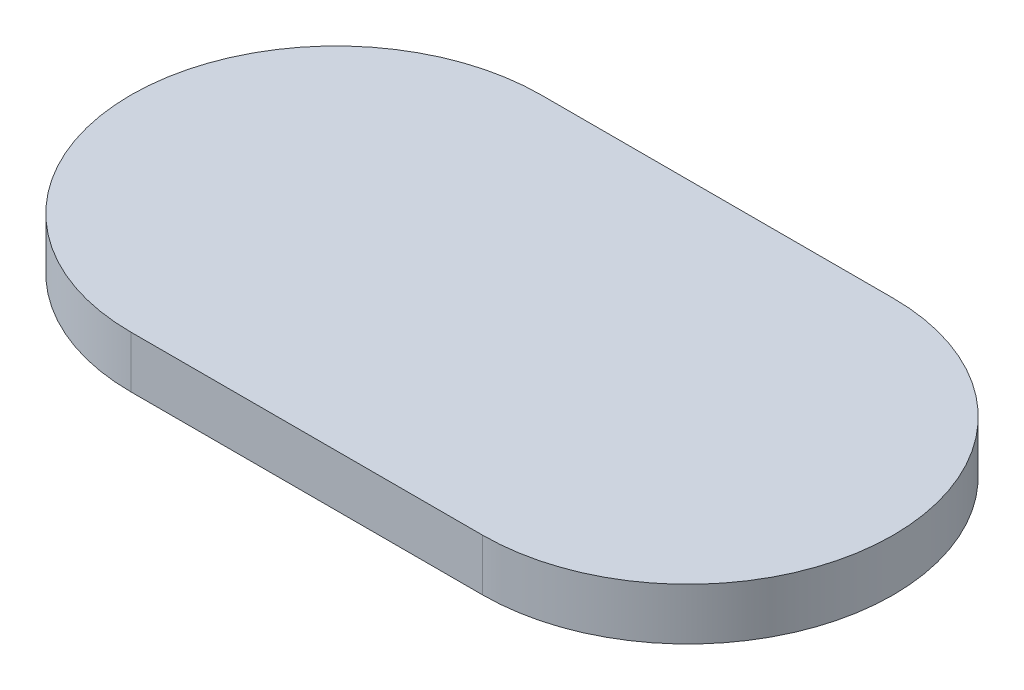
SolidWorks part; units mm, degrees
ref_plane "Plan de face" through (0, 0, 0) normal (0, 0, 1) x (1, 0, 0)
ref_plane "Plan de dessus" through (0, 0, 0) normal (0, 1, 0) x (1, 0, 0)
ref_plane "Plan de droite" through (0, 0, 0) normal (1, 0, 0) x (0, 0, -1)
sketch "Esquisse1" plane through (0, 0, 0) normal (0, 1, 0) x (1, 0, 0)
  line L0 (-37.4436, 0) -> (41.3534, 0) construction
  line L1 (0, 36.015) -> (0, -39.1729) construction
  line L2 (10.2, 0) -> (-10.2, 0) construction
  line L3 (10.2, -11.9) -> (-10.2, -11.9)
  line L4 (10.2, 11.9) -> (-10.2, 11.9)
  arc A0 (10.2, -11.9) -> (10.2, 11.9) centre (10.2, 0) ccw
  arc A1 (-10.2, 11.9) -> (-10.2, -11.9) centre (-10.2, 0) ccw
  point P7 (0, 0)
  dimension "D1" = 23.8
  dimension "D2" = 10.2
extrude "Boss.-Extru.1" add sketch "Esquisse1" along normal blind 3
sketch "Esquisse2" plane through (0, 0, 0) normal (0, -1, 0) x (1, 0, 0)
  line L2 (10.2, 11.9) -> (-10.2, 11.9)
  line L3 (-10.2, -11.9) -> (10.2, -11.9)
  line L4 (10.2, 11.9) -> (-10.2, 11.9)
  line L5 (-10.2, -11.9) -> (10.2, -11.9)
  circle A0 centre (-10.2, 0) radius 3.25
  circle A1 centre (10.2, 0) radius 1.75
  arc A2 (10.2, -11.9) -> (10.2, 11.9) centre (10.2, 0) ccw
  arc A3 (-10.2, 11.9) -> (-10.2, -11.9) centre (-10.2, 0) ccw
  arc A4 (10.2, -11.9) -> (10.2, 11.9) centre (10.2, 0) ccw
  arc A5 (-10.2, 11.9) -> (-10.2, -11.9) centre (-10.2, 0) ccw
  dimension "D2" = 3.5
  dimension "D3" = 6.5
  dimension "D1" = 0
extrude "Boss.-Extru.2" add sketch "Esquisse2" along normal blind 5 contours A0 | A1
sketch "Esquisse3" plane through (0, -5, 0) normal (0, -1, 0) x (1, 0, 0)
  circle A0 centre (-10.2, 0) radius 2.5
  circle A1 centre (-10.2, 0) radius 3.25
  circle A2 centre (-10.2, 0) radius 3.25
  circle A3 centre (10.2, 0) radius 1.75
  circle A4 centre (10.2, 0) radius 1.75
  circle A5 centre (10.2, 0) radius 1
  dimension "D3" = 2
  dimension "D4" = 5
  dimension "D1" = 0
  dimension "D2" = 0
extrude "Boss.-Extru.3" add sketch "Esquisse3" along normal blind 2.5 contours A0 | A5
